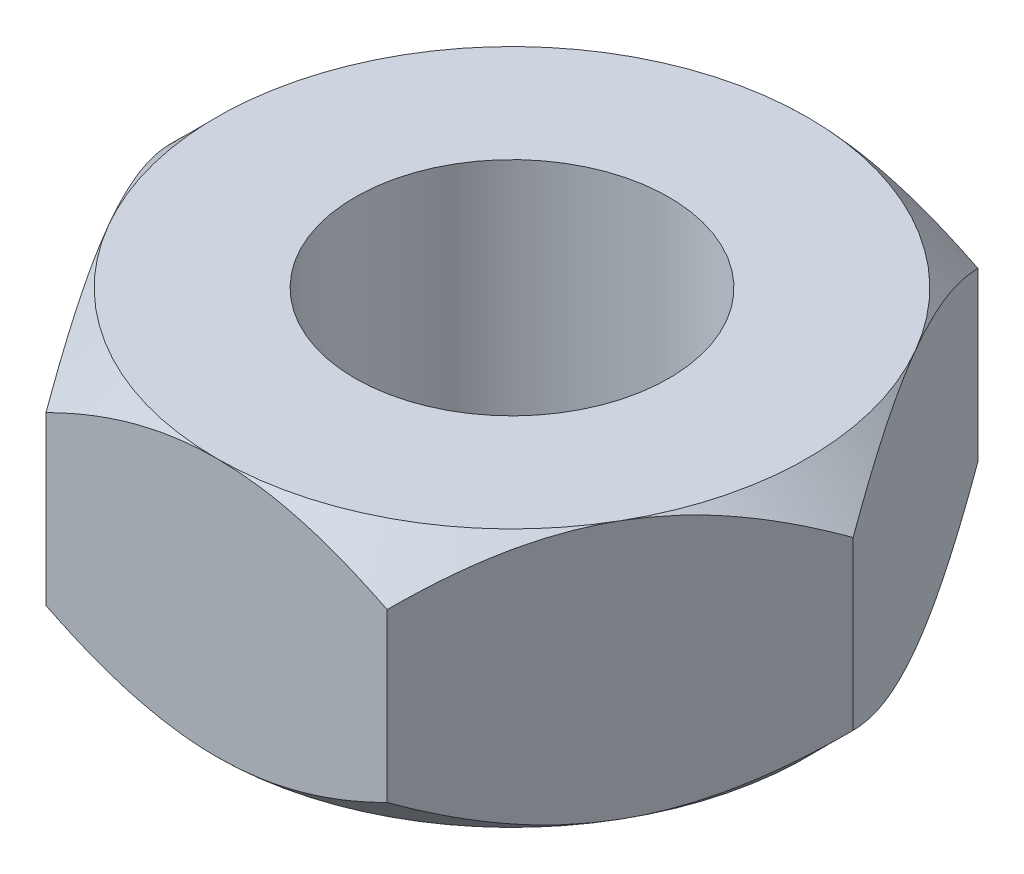
SolidWorks part; units mm, degrees
material "Stainless Steel (ferritic)"
ref_plane "Front Plane" through (0, 0, 0) normal (0, 0, 1) x (1, 0, 0)
ref_plane "Top Plane" through (0, 0, 0) normal (0, 1, 0) x (1, 0, 0)
ref_plane "Right Plane" through (0, 0, 0) normal (1, 0, 0) x (0, 0, -1)
sketch "Sketch1" plane through (0, 0, 0) normal (0, 1, 0) x (1, 0, 0)
  line L1 (7.3901, 0) -> (3.695, 6.4)
  line L2 (3.695, 6.4) -> (-3.695, 6.4)
  line L3 (-3.695, 6.4) -> (-7.3901, 0)
  line L4 (-7.3901, 0) -> (-3.695, -6.4)
  line L5 (-3.695, -6.4) -> (3.695, -6.4)
  line L6 (3.695, -6.4) -> (7.3901, 0)
  circle A0 centre (0, 0) radius 6.4 construction
  dimension "D1" = 12.8
extrude "Extrude1" add sketch "Sketch1" along normal blind 5.6
sketch "Sketch3" plane through (0, 5.6, 0) normal (0, 1, 0) x (1, 0, 0)
  line L0 (7.3901, 0) -> (3.695, 6.4) construction
  circle A0 centre (0, 0) radius 6.4
  circle A1 centre (0, 0) radius 12.4241
extrude "Extrude3" cut sketch "Sketch3" against normal blind 6.1 draft 45
sketch "Sketch4" plane through (0, 0, 0) normal (0, -1, 0) x (1, 0, 0)
  circle A1 centre (0, 0) radius 12.4241
  circle A2 centre (0, 0) radius 12.4241
  circle A3 centre (0, 0) radius 6.4
  circle A4 centre (0, 0) radius 6.4
  dimension "D1" = 0
  dimension "D2" = 0
extrude "Extrude4" cut sketch "Sketch4" against normal blind 6.1 draft 45
sketch "Sketch5" plane through (0, 5.6, 0) normal (0, 1, 0) x (1, 0, 0)
  line L0 (0, 0) -> (5.1307, 0)
hole_wizard "Tap Drill for M8x1.25 Tap1" positions "3DSketch1" profile "Sketch6" hole size "M8x1.25" standard "ANSI Metric"
sketch3d "3DSketch1"
  point P0 (0, 5.6, 0)
sketch "Sketch6" plane through (0, 5.6, 0) normal (1, 0, 0) x (0, 0, 1)
  line L0 (0, 0) -> (0, 12.0429)
  line L1 (0, 12.0429) -> (3.4, 10)
  line L2 (3.4, 10) -> (3.4, 0)
  line L5 (3.4, 0) -> (0, 0)
  line L10 (0, 12.0429) -> (-3.4, 10) construction
  line L11 (0, -6.35) -> (0, 107.95) construction
  dimension "Hole Dia." = 6.8
  dimension "Hole Depth" = 10
  dimension "Drill Angle" = 118
